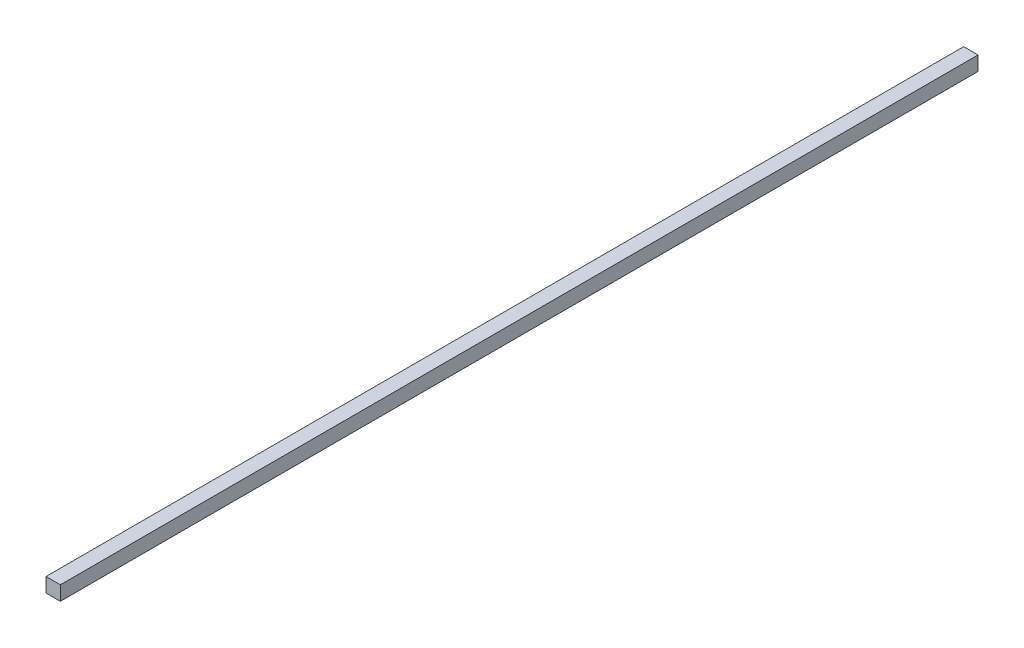
SolidWorks part; units mm, degrees
ref_plane "Front" through (0, 0, 0) normal (0, 0, 1) x (1, 0, 0)
ref_plane "Top" through (0, 0, 0) normal (0, 1, 0) x (1, 0, 0)
ref_plane "Right" through (0, 0, 0) normal (1, 0, 0) x (0, 0, -1)
sketch "Sketch1" plane through (0, 0, 0) normal (0, 0, 1) x (1, 0, 0)
  line L0 (-19.05, 19.05) -> (19.05, -19.05) construction
  line L1 (-19.05, 19.05) -> (19.05, 19.05)
  line L2 (-19.05, 19.05) -> (-19.05, -19.05)
  line L3 (-19.05, -19.05) -> (19.05, -19.05)
  line L4 (19.05, 19.05) -> (19.05, -19.05)
  dimension "D1" = 38.1
  dimension "D2" = 38.1
extrude "Extrude1" add sketch "Sketch1" along normal mid plane 2438.4
